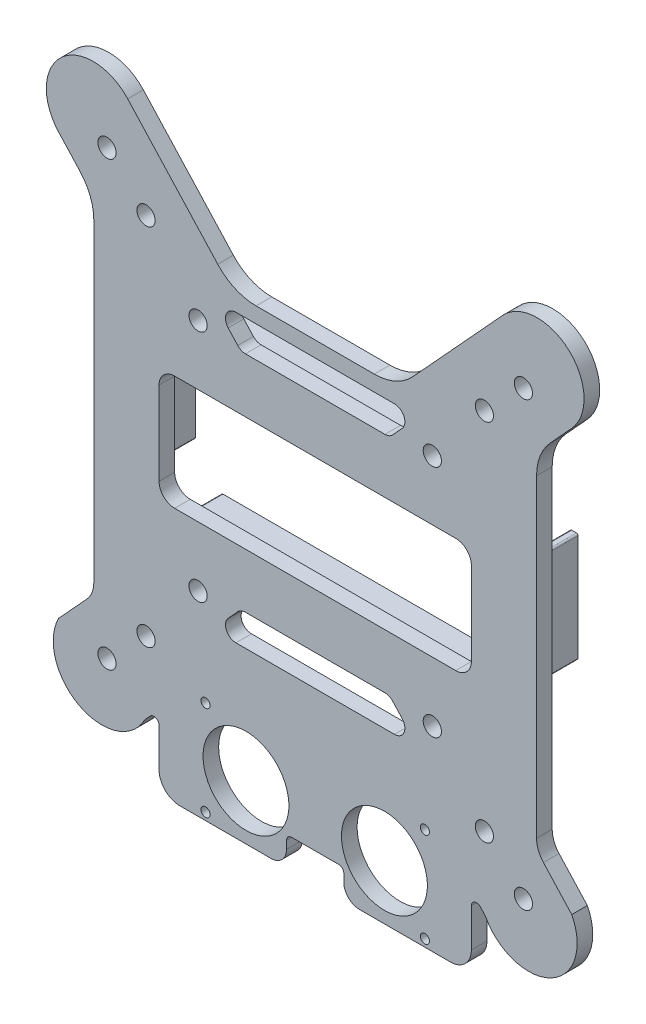
SolidWorks part; units mm, degrees
ref_plane "Alzado" through (0, 0, 0) normal (0, 0, 1) x (1, 0, 0)
ref_plane "Planta" through (0, 0, 0) normal (0, 1, 0) x (1, 0, 0)
ref_plane "Vista lateral" through (0, 0, 0) normal (1, 0, 0) x (0, 0, -1)
sketch "Croquis1" plane through (0, 0, 0) normal (0, 0, 1) x (1, 0, 0)
  line L0 (55, 120) -> (55, 0) construction
  line L1 (0, 0) -> (110, 0)
  line L2 (0, 0) -> (0, 120)
  line L3 (0, 120) -> (110, 120)
  line L4 (110, 0) -> (110, 120)
  line L5 (0, 60) -> (110, 60) construction
  line L6 (31, 85) -> (31, 76.9721) construction
  line L7 (80, 35) -> (30, 35) construction
  line L8 (80, 35) -> (80, 85) construction
  line L9 (80, 85) -> (30, 85) construction
  line L10 (30, 35) -> (30, 85) construction
  line L11 (80, 35) -> (30, 85) construction
  line L12 (80, 85) -> (30, 35) construction
  line L13 (30, 84) -> (42.8902, 84) construction
  line L15 (22.5, 95) -> (87.5, 95) construction
  line L16 (22.5, 95) -> (22.5, 25) construction
  line L17 (22.5, 25) -> (87.5, 25) construction
  line L18 (87.5, 95) -> (87.5, 25) construction
  line L19 (22.5, 95) -> (87.5, 25) construction
  line L20 (22.5, 25) -> (87.5, 95) construction
  line L21 (15, 102.5) -> (95, 102.5) construction
  line L22 (15, 102.5) -> (15, 17.5) construction
  line L23 (15, 17.5) -> (95, 17.5) construction
  line L24 (95, 102.5) -> (95, 17.5) construction
  line L25 (15, 102.5) -> (95, 17.5) construction
  line L26 (15, 17.5) -> (95, 102.5) construction
  circle A0 centre (32.5, 82.5) radius 1.5
  circle A5 centre (77.5, 82.5) radius 1.5
  circle A6 centre (77.5, 37.5) radius 1.5
  circle A7 centre (32.5, 37.5) radius 1.5
  circle A8 centre (95, 17.5) radius 1.75
  circle A9 centre (87.5, 25) radius 1.75
  circle A10 centre (22.5, 25) radius 1.75
  circle A11 centre (15, 17.5) radius 1.75
  circle A12 centre (87.5, 95) radius 1.75
  circle A13 centre (95, 102.5) radius 1.75
  circle A14 centre (15, 102.5) radius 1.75
  circle A15 centre (22.5, 95) radius 1.75
  point P9 (55, 60)
  point P20 (31, 82.5)
  point P21 (32.5, 84)
  point P22 (55, 60)
  point P28 (55, 60)
  point P35 (50, 85)
  point P44 (37, 51.5)
  dimension "D7" = 3
  dimension "D8" = 70
  dimension "D9" = 3.5
  dimension "D10" = 3.5
  dimension "D13" = 65
  dimension "D14" = 80
  dimension "D15" = 18
  dimension "D1" = 120
  dimension "D2" = 110
  dimension "D3" = 50
  dimension "D4" = 50
  dimension "D5" = 1
  dimension "D6" = 1
  dimension "D12" = 25
  dimension "D16" = 85
extrude "Saliente-Extruir1" add sketch "Croquis1" along normal blind 3
sketch "Croquis4" plane through (0, 0, 0) normal (0, 0, -1) x (-1, 0, 0)
  circle A0 centre (-32.5, 82.5) radius 1.5 construction
  circle A1 centre (-32.5, 37.5) radius 1.5 construction
  circle A2 centre (-77.5, 82.5) radius 1.5 construction
  circle A3 centre (-77.5, 37.5) radius 1.5 construction
  circle A4 centre (-32.5, 82.5) radius 1.5
  circle A5 centre (-32.5, 37.5) radius 1.5
  circle A6 centre (-77.5, 82.5) radius 1.5
  circle A7 centre (-77.5, 37.5) radius 1.5
  circle A8 centre (-32.5, 82.5) radius 1.75
  circle A9 centre (-32.5, 37.5) radius 1.75
  circle A10 centre (-77.5, 82.5) radius 1.75
  circle A11 centre (-77.5, 37.5) radius 1.75
  dimension "D1" = 0.25
extrude "Cortar-Extruir2" cut sketch "Croquis4" against normal blind 10
sketch "Croquis5" plane through (0, 0, 0) normal (0, 0, -1) x (-1, 0, 0)
  line L0 (-110, 60) -> (0, 60) construction
  line L1 (-22.5, 78) -> (-22.5, 77.5)
  line L2 (-23, 77) -> (-77, 77)
  line L3 (-55, 120) -> (-55, 0) construction
  line L4 (-110, 0) -> (-110, 120) construction
  line L9 (-17.5, 41.5) -> (-17.5, 78.5) construction
  line L10 (-19, 43) -> (-91, 43) construction
  line L11 (-19, 43) -> (-19, 77) construction
  line L12 (-19, 77) -> (-91, 77) construction
  line L13 (-91, 43) -> (-91, 77) construction
  line L14 (-110, 120) -> (0, 120) construction
  line L15 (0, 0) -> (-110, 0) construction
  line L16 (-17.5, 78.5) -> (-92.5, 78.5) construction
  line L17 (-92.5, 41.5) -> (-92.5, 78.5) construction
  line L18 (-17.5, 41.5) -> (-92.5, 41.5) construction
  line L19 (-92.2, 49.5) -> (-91.3, 49.5)
  line L20 (-91, 49.8) -> (-91, 70.2)
  line L21 (-91.3, 70.5) -> (-92.2, 70.5)
  line L22 (-92.5, 70.2) -> (-92.5, 49.8)
  line L23 (0, 120) -> (0, 0) construction
  line L24 (-55, 41.5) -> (-55, 78.5) construction
  line L25 (-17.5, 70.2) -> (-17.5, 49.8)
  line L26 (-18.7, 70.5) -> (-17.8, 70.5)
  line L27 (-19, 49.8) -> (-19, 70.2)
  line L28 (-17.8, 49.5) -> (-18.7, 49.5)
  line L29 (-76, 42.7) -> (-76, 41.8)
  line L30 (-75.7, 41.5) -> (-24.3, 41.5)
  line L31 (-24, 41.8) -> (-24, 42.7)
  line L32 (-24.3, 43) -> (-75.7, 43)
  line L33 (-77, 78.5) -> (-23, 78.5)
  line L34 (-77.5, 77.5) -> (-77.5, 78)
  arc A0 (-91.3, 70.5) -> (-91, 70.2) centre (-91.3, 70.2) cw
  arc A1 (-92.5, 70.2) -> (-92.2, 70.5) centre (-92.2, 70.2) cw
  arc A2 (-91, 49.8) -> (-91.3, 49.5) centre (-91.3, 49.8) cw
  arc A3 (-92.2, 49.5) -> (-92.5, 49.8) centre (-92.2, 49.8) cw
  arc A4 (-17.8, 49.5) -> (-17.5, 49.8) centre (-17.8, 49.8) ccw
  arc A5 (-19, 49.8) -> (-18.7, 49.5) centre (-18.7, 49.8) ccw
  arc A6 (-17.5, 70.2) -> (-17.8, 70.5) centre (-17.8, 70.2) ccw
  arc A7 (-18.7, 70.5) -> (-19, 70.2) centre (-18.7, 70.2) ccw
  arc A8 (-24, 42.7) -> (-24.3, 43) centre (-24.3, 42.7) ccw
  arc A9 (-24, 41.8) -> (-24.3, 41.5) centre (-24.3, 41.8) cw
  arc A10 (-75.7, 43) -> (-76, 42.7) centre (-75.7, 42.7) ccw
  arc A11 (-75.7, 41.5) -> (-76, 41.8) centre (-75.7, 41.8) cw
  arc A16 (-77, 77) -> (-77.5, 77.5) centre (-77, 77.5) cw
  arc A17 (-77.5, 78) -> (-77, 78.5) centre (-77, 78) cw
  arc A18 (-22.5, 78) -> (-23, 78.5) centre (-23, 78) ccw
  arc A19 (-22.5, 77.5) -> (-23, 77) centre (-23, 77.5) cw
  point P2 (-55, 60)
  point P29 (-91, 70.5)
  point P32 (-92.5, 70.5)
  point P35 (-91, 49.5)
  point P38 (-92.5, 49.5)
  point P51 (-17.5, 49.5)
  point P52 (-19, 49.5)
  point P53 (-17.5, 70.5)
  point P54 (-19, 70.5)
  point P61 (-24, 43)
  point P64 (-24, 41.5)
  point P67 (-76, 43)
  point P70 (-76, 41.5)
  point P89 (-55, 60)
  dimension "D6" = 0.3
  dimension "D9" = 0.3
  dimension "D12" = 0.5
  dimension "D14" = 0.5
  dimension "D1" = 72
  dimension "D2" = 34
  dimension "D3" = 1.5
  dimension "D4" = 8
  dimension "D5" = 8
  dimension "D7" = 15
  dimension "D8" = 5
  dimension "D11" = 17
  dimension "D13" = 15
  dimension "D15" = 5
extrude "Saliente-Extruir2" add sketch "Croquis5" along normal blind 10 contours L32 A10 L29 A11 L30 A9 L31 A8 | L2 A16 L34 A17 L33 A18 L1 A19 | L25 A4 L28 A5 L27 A7 L26 A6 | L20 A0 L21 A1 L22 A3 L19 A2
sketch "Croquis6" plane through (0, 0, 0) normal (0, 0, -1) x (-1, 0, 0)
  line L0 (-19, 43) -> (-91, 43) construction
  line L1 (-91, 49.8) -> (-91, 70.2) construction
  line L2 (-91, 43) -> (-91, 77) construction
  line L3 (-24.3, 43) -> (-75.7, 43) construction
  line L5 (-91, 77) -> (-19, 77) construction
  line L6 (-23, 77) -> (-77, 77) construction
  line L7 (-19, 77) -> (-19, 43) construction
  line L8 (-19, 49.8) -> (-19, 70.2) construction
  line L9 (-82, 71) -> (-28, 71)
  line L10 (-25, 68) -> (-25, 52)
  line L11 (-28, 49) -> (-82, 49)
  line L12 (-85, 52) -> (-85, 68)
  line L13 (-110, 120) -> (0, 0) construction
  line L14 (0, 120) -> (-110, 0) construction
  line L15 (-71.7099, 84.1486) -> (-69.8766, 82.1486)
  line L16 (-68.4023, 81.5) -> (-41.5977, 81.5)
  line L17 (-40.1234, 82.1486) -> (-38.2901, 84.1486)
  line L18 (-39.7644, 87.5) -> (-70.2356, 87.5)
  line L19 (-25, 71) -> (-25, 49) construction
  line L20 (-85, 71) -> (-25, 71) construction
  line L21 (-25, 49) -> (-85, 49) construction
  line L22 (-85, 49) -> (-85, 71) construction
  line L24 (-77, 78.5) -> (-23, 78.5) construction
  line L25 (-61.2053, 60) -> (-48.7947, 60) construction
  line L26 (-39.7644, 32.5) -> (-70.2356, 32.5)
  line L27 (-40.1234, 37.8514) -> (-38.2901, 35.8514)
  line L28 (-68.4023, 38.5) -> (-41.5977, 38.5)
  line L29 (-71.7099, 35.8514) -> (-69.8766, 37.8514)
  arc A0 (-25, 68) -> (-28, 71) centre (-28, 68) ccw
  arc A1 (-25, 52) -> (-28, 49) centre (-28, 52) cw
  arc A2 (-85, 52) -> (-82, 49) centre (-82, 52) ccw
  arc A3 (-85, 68) -> (-82, 71) centre (-82, 68) cw
  arc A4 (-38.2901, 84.1486) -> (-39.7644, 87.5) centre (-39.7644, 85.5) ccw
  arc A5 (-40.1234, 82.1486) -> (-41.5977, 81.5) centre (-41.5977, 83.5) cw
  arc A6 (-68.4023, 81.5) -> (-69.8766, 82.1486) centre (-68.4023, 83.5) cw
  arc A7 (-71.7099, 84.1486) -> (-70.2356, 87.5) centre (-70.2356, 85.5) cw
  arc A8 (-71.7099, 35.8514) -> (-70.2356, 32.5) centre (-70.2356, 34.5) ccw
  arc A9 (-68.4023, 38.5) -> (-69.8766, 37.8514) centre (-68.4023, 36.5) ccw
  arc A10 (-40.1234, 37.8514) -> (-41.5977, 38.5) centre (-41.5977, 36.5) ccw
  arc A11 (-38.2901, 35.8514) -> (-39.7644, 32.5) centre (-39.7644, 34.5) cw
  point P54 (-55, 60)
  point P55 (-55, 60)
  dimension "D2" = 3
  dimension "D3" = 2
  dimension "D4" = 6
  dimension "D5" = 3
  dimension "D6" = 4
  dimension "D7" = 4
  dimension "D1" = 6
extrude "Cortar-Extruir3" cut sketch "Croquis6" against normal blind 10 contours A7 A6 L16 A5 A4 L18 | A3 L12 A2 L11 A1 L10 A0 L9 | A11 A10 L28 A9 A8 L26
sketch "Croquis7" plane through (0, 0, 0) normal (0, 0, -1) x (-1, 0, 0)
  line L0 (-77.5, 10.5) -> (-32.5, 10.5) construction
  line L5 (-77.5, 21) -> (-32.5, 21) construction
  line L11 (-77.5, 21) -> (-77.5, 0) construction
  line L12 (-77.5, 0) -> (-32.5, 0) construction
  line L13 (-32.5, 21) -> (-32.5, 0) construction
  line L14 (-55, 21) -> (-55, 0) construction
  line L15 (0, 0) -> (-110, 0) construction
  line L17 (-33.3, 0.8) -> (-76.7, 0.8) construction
  line L18 (-33.3, 0.8) -> (-33.3, 20.2) construction
  line L19 (-33.3, 20.2) -> (-76.7, 20.2) construction
  line L20 (-76.7, 0.8) -> (-76.7, 20.2) construction
  line L21 (-33.3, 0.8) -> (-76.7, 20.2) construction
  line L22 (-33.3, 20.2) -> (-76.7, 0.8) construction
  line L27 (-49.5, 0) -> (-49.5, 4.5)
  line L28 (-60.5, 0) -> (-49.5, 0)
  line L29 (-60.5, 0) -> (-60.5, 4.5)
  line L30 (-50.5, 5.5) -> (-59.5, 5.5)
  circle A1 centre (-76.075, 19.575) radius 0.625 construction
  circle A2 centre (-76.075, 1.425) radius 0.625 construction
  circle A3 centre (-76.075, 19.575) radius 0.875
  circle A4 centre (-76.075, 1.425) radius 0.875
  circle A5 centre (-33.925, 1.425) radius 0.875
  circle A6 centre (-33.925, 19.575) radius 0.875
  circle A7 centre (-68.3, 10.5) radius 8 construction
  circle A8 centre (-41.7, 10.5) radius 8 construction
  circle A9 centre (-68.3, 10.5) radius 8.25
  circle A10 centre (-41.7, 10.5) radius 8.25
  arc A19 (-59.5, 5.5) -> (-60.5, 4.5) centre (-59.5, 4.5) ccw
  arc A20 (-50.5, 5.5) -> (-49.5, 4.5) centre (-50.5, 4.5) cw
  point P10 (-55, 0)
  point P11 (-55, 10.5)
  point P12 (-55, 10.5)
  point P19 (-76.075, 20.2)
  point P20 (-76.7, 19.575)
  point P21 (-76.075, 20.2)
  point P36 (-76.3, 10.5)
  point P37 (-60.3, 10.5)
  point P38 (-49.7, 10.5)
  point P39 (-33.7, 10.5)
  point P50 (-60.5, 21)
  point P53 (-49.5, 21)
  dimension "D5" = 0.8
  dimension "D7" = 0.25
  dimension "D8" = 0.25
  dimension "D10" = 16
  dimension "D11" = 1.2
  dimension "D15" = 11
  dimension "D12" = 1.2
  dimension "D17" = 1
  dimension "D14" = 5.5
  dimension "D6" = 1.25
  dimension "D9" = 16
  dimension "D2" = 45
  dimension "D3" = 21
  dimension "D4" = 0.8
  dimension "D13" = 0.25
  dimension "D16" = 5.5
extrude "Cortar-Extruir5" cut sketch "Croquis7" against normal blind 10 contours A20 L30 A19 L29 L28 L27
fillet "Redondeo4" radius 3 2 edges at (49.5, 0, 1.5) (60.5, 0, 1.5)
sketch "Croquis9" plane through (0, 0, 0) normal (0, 0, -1) x (-1, 0, 0)
  line L0 (-39.7644, 87.5) -> (-70.2356, 87.5) construction
  line L1 (-66.3502, 90.5) -> (-43.6498, 90.5)
  line L2 (-36.2783, 93.7428) -> (-18.979, 112.6146)
  line L3 (0, 0) -> (-110, 120) construction
  line L4 (-29, 0) -> (0, 0)
  line L5 (-5.7103, 100.4516) -> (-9.8391, 95.9474)
  line L6 (-12.4675, 89.1902) -> (-12.4675, 28.8649)
  line L7 (-11.1533, 25.4863) -> (-5.7103, 19.5484)
  line L8 (-25, 4) -> (-25, 11.3829)
  line L10 (-23.2628, 12.0586) -> (-22.2971, 11.0051)
  line L11 (0, 0) -> (-46.5, 0) construction
  line L12 (-110, 0) -> (0, 120) construction
  line L13 (-18.979, 112.6146) -> (-5.7103, 100.4516) construction
  line L14 (-55, 120) -> (-55, 5.5) construction
  line L15 (-110, 120) -> (0, 120) construction
  line L16 (-50.5, 5.5) -> (-59.5, 5.5) construction
  line L17 (-5.7103, 19.5484) -> (-22.2971, 11.0051) construction
  line L18 (0, 120) -> (0, 0) construction
  line L19 (-104.2897, 19.5484) -> (-87.7029, 11.0051) construction
  line L20 (0, 0) -> (0, 120)
  line L21 (0, 120) -> (-110, 120)
  line L22 (-91.021, 112.6146) -> (-104.2897, 100.4516) construction
  line L23 (0, 0) -> (-110, 120) construction
  line L24 (-110, 0) -> (0, 120) construction
  line L25 (-110, 0) -> (-110, 120)
  line L26 (-86.7372, 12.0586) -> (-87.7029, 11.0051)
  line L27 (-85, 4) -> (-85, 11.3829)
  line L28 (-98.8467, 25.4863) -> (-104.2897, 19.5484)
  line L29 (-97.5325, 89.1902) -> (-97.5325, 28.8649)
  line L30 (-104.2897, 100.4516) -> (-100.1609, 95.9474)
  line L31 (-81, 0) -> (-110, 0)
  line L32 (-73.7217, 93.7428) -> (-91.021, 112.6146)
  arc A0 (-18.979, 112.6146) -> (-5.7103, 100.4516) centre (-12.3447, 106.5331) cw
  arc A1 (-12.4675, 89.1902) -> (-9.8391, 95.9474) centre (-2.4675, 89.1902) cw
  arc A2 (-22.2971, 11.0051) -> (-5.7103, 19.5484) centre (-14.0037, 15.2767) ccw
  arc A3 (-43.6498, 90.5) -> (-36.2783, 93.7428) centre (-43.6498, 100.5) ccw
  arc A4 (-25, 11.3829) -> (-23.2628, 12.0586) centre (-24, 11.3829) cw
  arc A5 (-25, 4) -> (-29, 0) centre (-29, 4) cw
  arc A6 (-11.1533, 25.4863) -> (-12.4675, 28.8649) centre (-7.4675, 28.8649) cw
  arc A7 (-98.8467, 25.4863) -> (-97.5325, 28.8649) centre (-102.5325, 28.8649) ccw
  arc A8 (-85, 4) -> (-81, 0) centre (-81, 4) ccw
  arc A9 (-85, 11.3829) -> (-86.7372, 12.0586) centre (-86, 11.3829) ccw
  arc A10 (-66.3502, 90.5) -> (-73.7217, 93.7428) centre (-66.3502, 100.5) cw
  arc A11 (-87.7029, 11.0051) -> (-104.2897, 19.5484) centre (-95.9963, 15.2767) cw
  arc A12 (-97.5325, 89.1902) -> (-100.1609, 95.9474) centre (-107.5325, 89.1902) ccw
  arc A13 (-91.021, 112.6146) -> (-104.2897, 100.4516) centre (-97.6553, 106.5331) ccw
  point P22 (-97.5325, 26.92)
  point P27 (-12.4675, 93.08)
  point P32 (-39.2508, 90.5)
  point P43 (-25, 13.9537)
  point P47 (-12.4675, 26.92)
  point P69 (-55, 90.5)
  point P70 (-85, 13.9537)
  point P71 (-70.7492, 90.5)
  point P72 (-97.5325, 93.08)
  dimension "D6" = 10
  dimension "D9" = 10
  dimension "D12" = 10
  dimension "D14" = 1
  dimension "D13" = 4
  dimension "D16" = 5
  dimension "D1" = 3
  dimension "D2" = 18
  dimension "D3" = 9
  dimension "D4" = 10
  dimension "D5" = 30
  dimension "D7" = 18
  dimension "D8" = 9
  dimension "D10" = 4
  dimension "D11" = 25
  dimension "D15" = 29
extrude "Cortar-Extruir6" cut sketch "Croquis9" against normal blind 10
